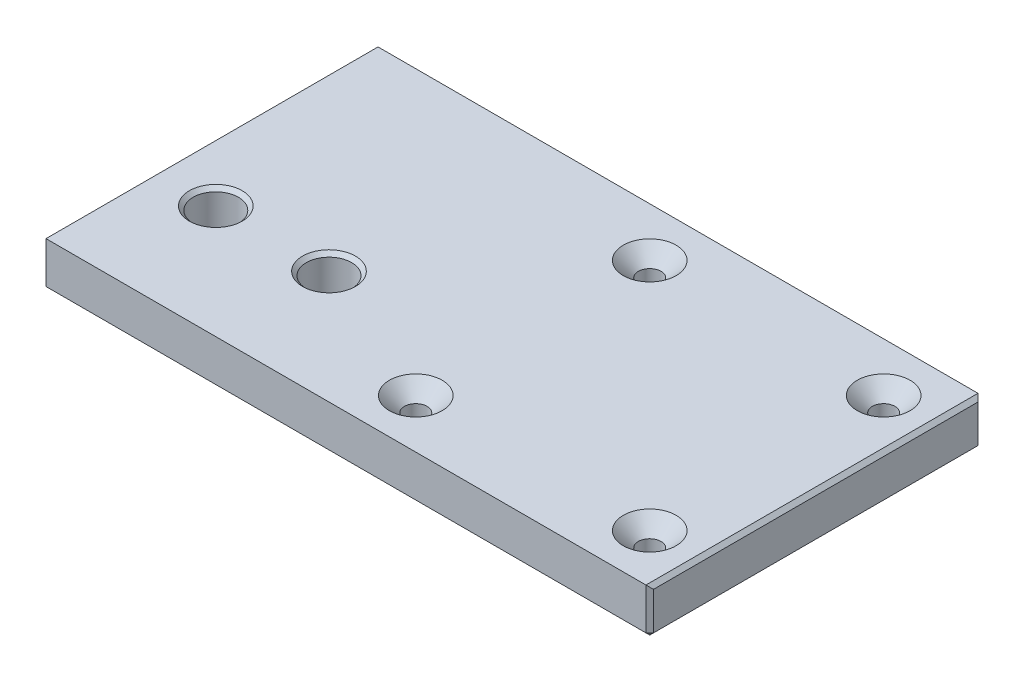
SolidWorks part; units mm, degrees
ref_plane "Alzado" through (0, 0, 0) normal (0, 0, 1) x (1, 0, 0)
ref_plane "Planta" through (0, 0, 0) normal (0, 1, 0) x (1, 0, 0)
ref_plane "Vista lateral" through (0, 0, 0) normal (1, 0, 0) x (0, 0, -1)
sketch "Croquis1" plane through (0, 0, 0) normal (0, 1, 0) x (1, 0, 0)
  line L1 (-32.7283, 20.7785) -> (47.7717, 20.7785)
  line L2 (-32.7283, 20.7785) -> (-32.7283, -23.2215)
  line L3 (-32.7283, -23.2215) -> (47.7717, -23.2215)
  line L4 (47.7717, 20.7785) -> (47.7717, -23.2215)
  circle A0 centre (10.2717, 14.2785) radius 1.5
  circle A1 centre (41.2717, 14.2785) radius 1.5
  circle A2 centre (10.2717, -16.7215) radius 1.5
  circle A3 centre (41.2717, -16.7215) radius 1.5
  circle A4 centre (-24.7283, -8.2215) radius 3
  circle A5 centre (-9.7283, -8.2215) radius 3
  dimension "D7" = 3
  dimension "D8" = 6
  dimension "D9" = 6
  dimension "D10" = 3
  dimension "D11" = 3
  dimension "D12" = 3
  dimension "D1" = 44
  dimension "D2" = 20
  dimension "D3" = 31
  dimension "D4" = 31
  dimension "D5" = 6.5
  dimension "D6" = 6.5
  dimension "D13" = 15
  dimension "D14" = 8
  dimension "D16" = 15
extrude "Saliente-Extruir1" add sketch "Croquis1" along normal blind 6
chamfer "Chaflán1" distance 0.5 angle 45 18 edges at (41.2717, 0, 18.2215) (41.2717, 0, -12.7785) (10.2717, 0, -12.7785) (10.2717, 0, 18.2215) (-32.7283, 3, -20.7785) (-32.7283, 3, 23.2215) (47.7717, 3, 23.2215) (7.5217, 0, 23.2215) (47.7717, 0, 1.2215) (-32.7283, 0, 1.2215) (7.5217, 0, -20.7785) (47.7717, 3, -20.7785) (47.7717, 6, 1.2215) (-32.7283, 6, 1.2215) (-9.7283, 0, 11.2215) (-24.7283, 0, 11.2215) (-9.7283, 6, 11.2215) (-24.7283, 6, 11.2215)
chamfer "Chaflán2" distance 2 angle 45 4 edges at (10.2717, 6, 18.2215) (10.2717, 6, -12.7785) (41.2717, 6, 18.2215) (41.2717, 6, -12.7785)
